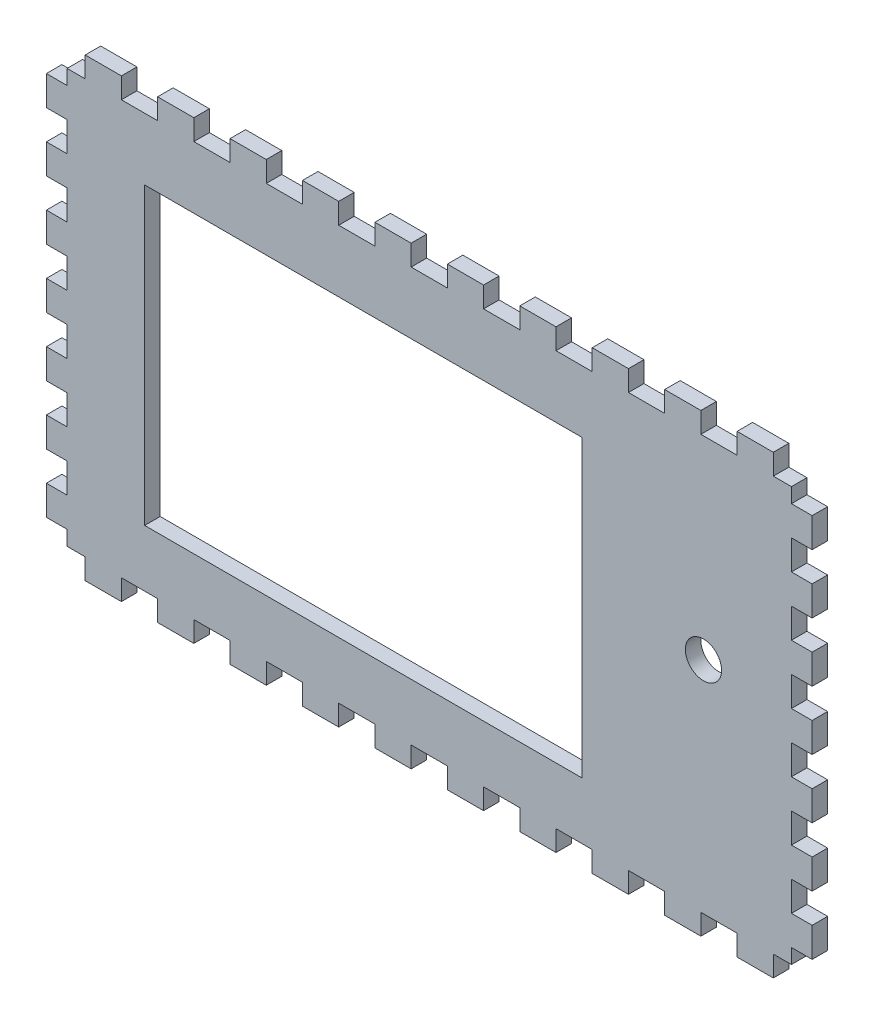
SolidWorks part; units mm, degrees
ref_plane "Piano frontale" through (0, 0, 0) normal (0, 0, 1) x (1, 0, 0)
ref_plane "Piano superiore" through (0, 0, 0) normal (0, 1, 0) x (1, 0, 0)
ref_plane "Piano destro" through (0, 0, 0) normal (1, 0, 0) x (0, 0, -1)
sketch "Schizzo1" plane through (0, 0, 0) normal (0, 0, 1) x (1, 0, 0)
  line L1 (0, 0) -> (140, 0)
  line L2 (0, 0) -> (0, 80)
  line L3 (0, 80) -> (140, 80)
  line L4 (140, 0) -> (140, 80)
  line L5 (12, 9) -> (107, 9)
  line L6 (12, 9) -> (12, 70)
  line L7 (12, 70) -> (107, 70)
  line L8 (107, 9) -> (107, 70)
  circle A0 centre (123, 42.5) radius 3.5
  dimension "D7" = 7
  dimension "D1" = 140
  dimension "D2" = 80
  dimension "D3" = 10
  dimension "D4" = 95
  dimension "D5" = 61
  dimension "D6" = 33
  dimension "D8" = 16
  dimension "D9" = 27.5
extrude "Estrusione-Estrusione1" add sketch "Schizzo1" along normal blind 3
sketch "Schizzo2" plane through (0, 0, 3) normal (0, 0, 1) x (1, 0, 0)
  line L0 (0, 80) -> (0, 0) construction
  line L1 (3.5, 80) -> (10.5, 80)
  line L2 (3.5, 80) -> (3.5, 84)
  line L3 (3.5, 84) -> (10.5, 84)
  line L4 (10.5, 80) -> (10.5, 84)
  line L5 (3.5, 0) -> (10.5, 0)
  line L6 (3.5, 0) -> (3.5, -4)
  line L7 (3.5, -4) -> (10.5, -4)
  line L8 (10.5, 0) -> (10.5, -4)
  line L9 (140, 80) -> (0, 80) construction
  line L10 (0, 0) -> (140, 0) construction
  dimension "D1" = 7
  dimension "D2" = 4
  dimension "D4" = 4
  dimension "D3" = 3.5
extrude "Estrusione-Estrusione2" add sketch "Schizzo2" against normal blind 3
pattern_linear "Ripetizione a L1" count 10 spacing 14 along (1, 0, 0) of "Estrusione-Estrusione2"
sketch "Schizzo3" plane through (0, 0, 3) normal (0, 0, 1) x (1, 0, 0)
  line L0 (0, 80) -> (0, 0) construction
  line L1 (0, 77.1429) -> (-4, 77.1429)
  line L2 (0, 77.1429) -> (0, 71.4286)
  line L3 (0, 71.4286) -> (-4, 71.4286)
  line L4 (-4, 77.1429) -> (-4, 71.4286)
  line L5 (140, 0) -> (140, 80) construction
  line L6 (140, 77.1429) -> (144, 77.1429)
  line L7 (140, 77.1429) -> (140, 71.4286)
  line L8 (140, 71.4286) -> (144, 71.4286)
  line L9 (144, 77.1429) -> (144, 71.4286)
  line L10 (140, 80) -> (136.5, 80) construction
  dimension "D4" = 4
  dimension "D1" = 5.7143
  dimension "D2" = 2.8571
  dimension "D3" = 4
extrude "Estrusione-Estrusione3" add sketch "Schizzo3" against normal blind 3
pattern_linear "Ripetizione a L2" count 7 spacing 11.4286 along (0, -1, 0) of "Estrusione-Estrusione3"
sketch "Schizzo4" plane through (0, 0, 3) normal (0, 0, 1) x (1, 0, 0)
  line L1 (12, 70) -> (107, 70)
  line L2 (12, 70) -> (12, 9)
  line L3 (12, 9) -> (107, 9)
  line L4 (107, 70) -> (107, 9)
  line L5 (15, 68) -> (99.5, 68)
  line L6 (15, 68) -> (15, 11)
  line L7 (15, 11) -> (99.5, 11)
  line L8 (99.5, 68) -> (99.5, 11)
  dimension "D1" = 3
  dimension "D2" = 2
  dimension "D3" = 2
  dimension "D4" = 7.5
extrude "Estrusione-Estrusione4" add sketch "Schizzo4" against normal blind 3
equation "\"WFront\"= 140mm"
equation "\"HFront\"= 80mm"
equation "\"DFront\"= 4mm"
equation "\"WLeft\"= 50mm"
equation "\"HLeft\"= 80mm"
equation "\"DLeft\"= 4mm"
equation "\"WTop\"= 140mm"
equation "\"HTop\"= 50mm"
equation "\"DTop\"= 4mm"
equation "\"N_Denti_W\"= 10"
equation "\"N_Denti_H\"= 7"
equation "\"N_Denti_D\"= 4"
equation "\"HDistDenti\"= \"HFront\" / \"N_Denti_H\""
equation "\"WDistDenti\"= \"WFront\" / \"N_Denti_W\""
equation "\"DDistDenti\"= \"WLeft\" / \"N_Denti_D\""
equation "\"HDenti\"= \"HDistDenti\" / 2"
equation "\"WDenti\"= \"WDistDenti\" / 2"
equation "\"DDenti\"= \"DDistDenti\" / 2"
equation "\"WDisplay\"= 95mm"
equation "\"HDisplay\"= 61mm"
equation "\"CEnc\"= 7mm"
equation "\"Display_to_Enc_W\"= 11.5 + \"CEnc\" / 2"
equation "\"Display_to_Dx\"= 32mm"
equation "\"Display_to_Top\"= 10mm"
equation "\"Display_to_Enc_H\"= 24 + \"CEnc\" / 2"
equation "\"D1@Schizzo1\"=\"WFront\""
equation "\"D2@Schizzo1\"=\"HFront\""
equation "\"D3@Schizzo1\"=\"Display_to_Top\""
equation "\"D4@Schizzo1\"=\"WDisplay\""
equation "\"D5@Schizzo1\"=\"HDisplay\""
equation "\"D7@Schizzo1\"=\"CEnc\""
equation "\"D1@Estrusione-Estrusione1\"=\"DMask\""
equation "\"D1@Schizzo2\"=\"WDenti\""
equation "\"D2@Schizzo2\"=\"DTop\""
equation "\"D4@Schizzo2\"=\"DTop\""
equation "\"D1@Estrusione-Estrusione2\"=\"DMask\""
equation "\"D3@Ripetizione a L1\"=\"WDistDenti\""
equation "\"D1@Ripetizione a L1\"=\"N_Denti_W\""
equation "\"D3@Schizzo2\"=\"WDenti\"/2"
equation "\"D1@Schizzo3\"=\"HDenti\""
equation "\"D2@Schizzo3\"=\"HDenti\"/2"
equation "\"D3@Schizzo3\"=\"DLeft\""
equation "\"D4@Schizzo3\"=\"DLeft\""
equation "\"D1@Estrusione-Estrusione3\"=\"DMask\""
equation "\"D3@Ripetizione a L2\"=\"HDistDenti\""
equation "\"D1@Ripetizione a L2\"=\"N_Denti_H\""
equation "\"DMask\"= 3mm"
equation "\"D1@Estrusione-Estrusione4\"=\"DMask\""
